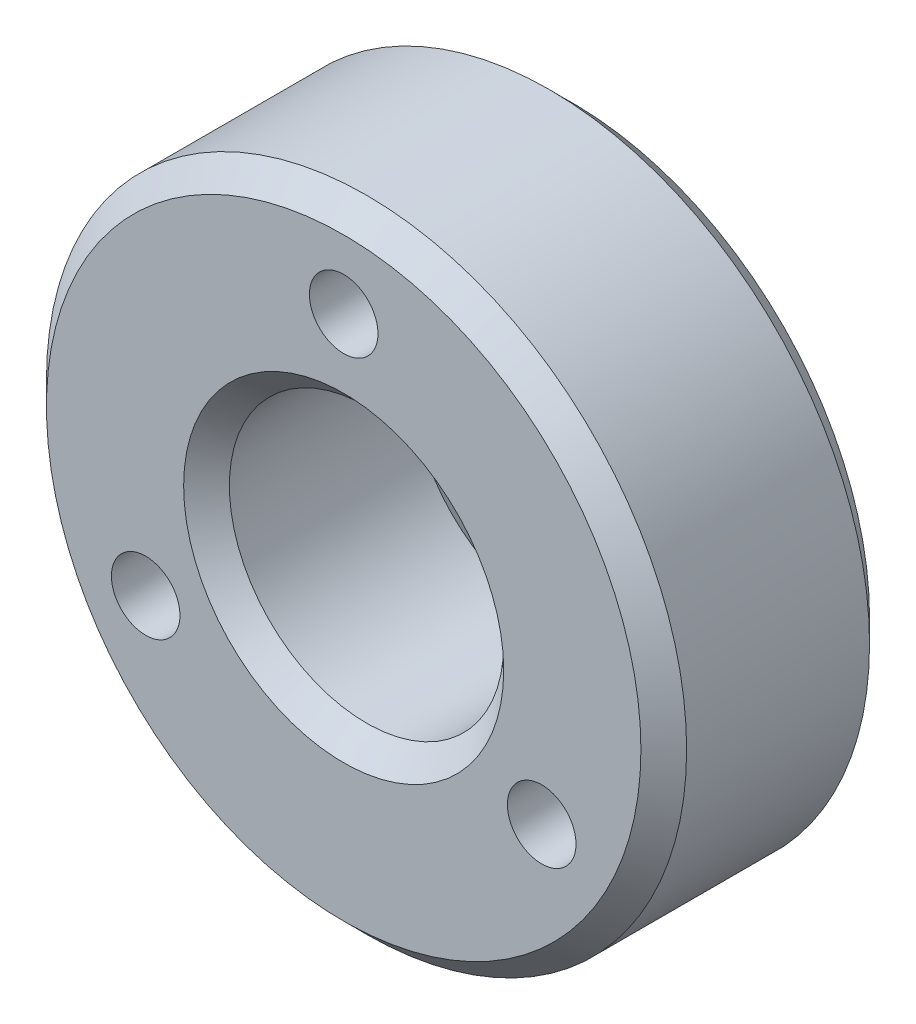
SolidWorks part; units mm, degrees
material "ABS"
ref_plane "Front Plane" through (0, 0, 0) normal (0, 0, 1) x (1, 0, 0)
ref_plane "Top Plane" through (0, 0, 0) normal (0, 1, 0) x (1, 0, 0)
ref_plane "Right Plane" through (0, 0, 0) normal (1, 0, 0) x (0, 0, -1)
sketch "Sketch1" plane through (0, 0, 0) normal (0, 0, 1) x (1, 0, 0)
  circle A0 centre (0, 0) radius 14
  circle A1 centre (0, 0) radius 6
  circle A2 centre (0, 10) radius 1.5
  circle A3 centre (8.6603, -5) radius 1.5
  circle A4 centre (-8.6603, -5) radius 1.5
  point P13 (0, 0)
  dimension "D1" = 12
  dimension "D2" = 28
  dimension "D3" = 3
  dimension "D4" = 10
  dimension "D5" = 3
extrude "Boss-Extrude1" add sketch "Sketch1" along normal blind 10
chamfer "Chamfer1" distance 1 angle 45 4 edges at (14, 0, 10) (14, 0, 0) (6, 0, 0) (6, 0, 10)
